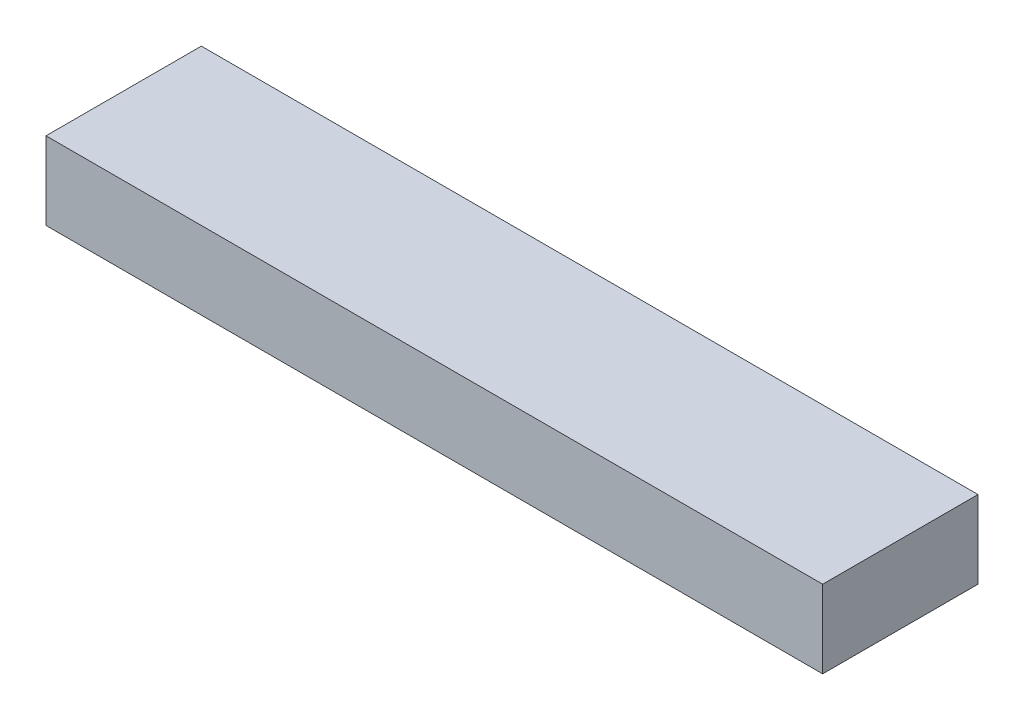
SolidWorks part; units mm, degrees
ref_plane "Přední rovina" through (0, 0, 0) normal (0, 0, 1) x (1, 0, 0)
ref_plane "Horní rovina" through (0, 0, 0) normal (0, 1, 0) x (1, 0, 0)
ref_plane "Pravá rovina" through (0, 0, 0) normal (1, 0, 0) x (0, 0, -1)
sketch "Sketch1" plane through (0, 0, 0) normal (0, 0, 1) x (1, 0, 0)
  line L1 (0, 0) -> (100, 0)
  line L2 (0, 0) -> (0, 10)
  line L3 (0, 10) -> (100, 10)
  line L4 (100, 0) -> (100, 10)
  dimension "D1" = 100
  dimension "D2" = 10
extrude "Boss-Extrude1" add sketch "Sketch1" along normal blind 20
